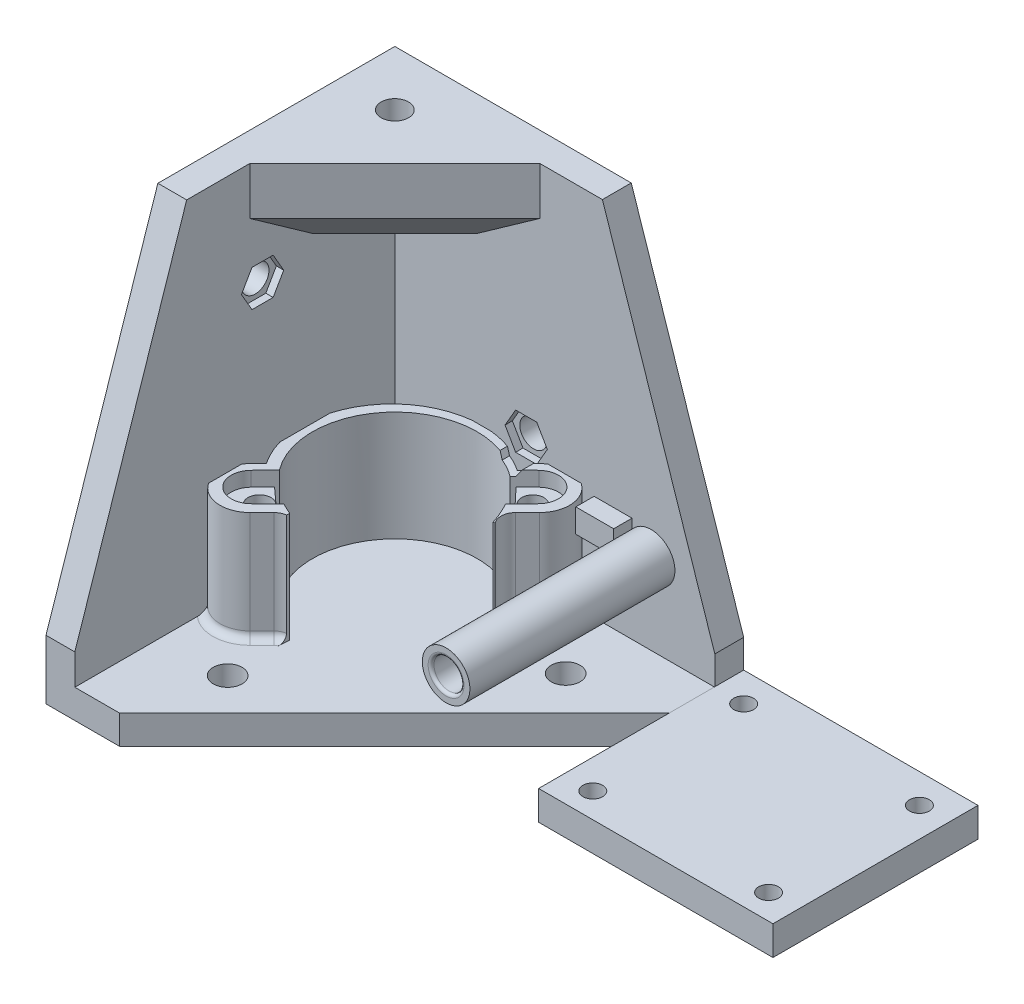
SolidWorks part; units mm, degrees
ref_plane "Front" through (0, 0, 0) normal (0, 0, 1) x (1, 0, 0)
ref_plane "Top" through (0, 0, 0) normal (0, 1, 0) x (1, 0, 0)
ref_plane "Right" through (0, 0, 0) normal (1, 0, 0) x (0, 0, -1)
sketch "Sketch1" plane through (0, 0, 0) normal (0, 1, 0) x (1, 0, 0)
  line L0 (0, 0) -> (0, 60.5)
  line L1 (0, -55) -> (0, 55) construction
  line L2 (0, 60.5) -> (60.5, 60.5)
  line L3 (60.5, 60.5) -> (60.5, 47.75)
  line L4 (60.5, 47.75) -> (12.75, 0)
  line L5 (-55, 0) -> (55, 0) construction
  line L6 (12.75, 0) -> (0, 0)
  dimension "D1" = 60.5
  dimension "D2" = 12.75
extrude "Boss-Extrude1" add sketch "Sketch1" along normal blind 5
sketch "Sketch4" plane through (0, 0, 0) normal (-1, 0, 0) x (0, 0, 1)
  line L0 (-60.5, 5) -> (-60.5, 68.5)
  line L1 (-60.5, 68.5) -> (-19.4, 68.5)
  line L2 (-19.4, 68.5) -> (0, 10.3086)
  line L3 (0, 10.3086) -> (0, 5)
  line L4 (0, -2.75) -> (0, 2.75) construction
  line L5 (-60.5, 5) -> (0, 5) construction
  line L6 (-60.5, 5) -> (0, 5)
  dimension "D1" = 63.5
  dimension "D2" = 41.1
  dimension "D3" = 61.34
extrude "Boss-Extrude2" add sketch "Sketch4" against normal blind 5
sketch "Sketch5" plane through (0, 0, -60.5) normal (0, 0, -1) x (-1, 0, 0)
  line L0 (0, 68.5) -> (-41, 68.5)
  line L1 (-41, 68.5) -> (-60.5, 10.0047)
  line L2 (-60.5, 10.0047) -> (-60.5, 5)
  line L6 (-60.5, 0) -> (0, 0)
  line L7 (0, 0) -> (0, 68.5)
  line L8 (0, 68.5) -> (-5, 68.5)
  line L9 (-5, 68.5) -> (-5, 5)
  line L10 (-5, 5) -> (-60.5, 5)
  line L11 (-60.5, 5) -> (-60.5, 0)
  line L12 (-60.5, 0) -> (0, 0)
  line L13 (0, 0) -> (0, 68.5)
  line L14 (0, 68.5) -> (-5, 68.5)
  line L15 (-5, 68.5) -> (-5, 5)
  line L16 (-5, 5) -> (-60.5, 5)
  line L17 (-60.5, 5) -> (-60.5, 0)
  line M13 (-5, 68.5) -> (-5, 5)
  line M14 (-5, 5) -> (-60.5, 5)
  dimension "D2" = 41
  dimension "D3" = 61.66
  dimension "D1" = 0
extrude "Boss-Extrude3" add sketch "Sketch5" against normal blind 5 contours L1 L2 L0 M14 M13
sketch "Sketch6" plane through (0, 5, 0) normal (0, 1, 0) x (1, 0, 0)
  line L0 (60.5, 60.5) -> (0, 60.5) construction
  line L4 (0, 19.4) -> (0, 0)
  line L5 (60.5, 55.5) -> (5, 55.5)
  line L6 (5, 55.5) -> (5, 0)
  line L7 (5, 0) -> (12.75, 0)
  line L8 (12.75, 0) -> (60.5, 47.75)
  line L9 (60.5, 47.75) -> (60.5, 55.5)
  line L10 (60.5, 55.5) -> (5, 55.5)
  line L11 (5, 55.5) -> (5, 0)
  line L12 (5, 0) -> (12.75, 0)
  line L13 (12.75, 0) -> (60.5, 47.75)
  line L14 (60.5, 47.75) -> (60.5, 55.5)
  line L15 (0, 0) -> (5, 0)
  line L16 (5, 0) -> (5, 19.4)
  line L17 (5, 19.4) -> (0, 19.4)
  line L18 (0, 19.4) -> (0, 0)
  line L19 (0, 0) -> (5, 0)
  line L20 (5, 0) -> (5, 19.4)
  line L21 (5, 19.4) -> (0, 19.4)
  line L24 (0, 60.5) -> (0, 19.4)
  line L25 (0, 19.4) -> (5, 19.4)
  line L26 (5, 19.4) -> (5, 55.5)
  line L27 (5, 55.5) -> (41, 55.5)
  line L28 (41, 55.5) -> (41, 60.5)
  line L29 (41, 60.5) -> (0, 60.5)
  line L30 (0, 60.5) -> (0, 19.4)
  line L31 (0, 19.4) -> (5, 19.4)
  line L32 (5, 19.4) -> (5, 55.5)
  line L33 (5, 55.5) -> (41, 55.5)
  line L34 (41, 55.5) -> (41, 60.5)
  line L35 (41, 60.5) -> (0, 60.5)
  circle A0 centre (16.5, 15) radius 2.5
  circle A1 centre (45.5, 44.625) radius 2.5
  dimension "D1" = 5
  dimension "D2" = 5
  dimension "D3" = 0
  dimension "D4" = 15
  dimension "D6" = 16.5
  dimension "D7" = 15
  dimension "D9" = 15.875
  dimension "D5" = 0
  dimension "D8" = 0
extrude "Cut-Extrude1" cut sketch "Sketch6" against normal through all contours A0 | A1
sketch "Sketch9" plane through (0, 0, -55.5) normal (0, 0, 1) x (1, 0, 0)
  line L1 (5, 68.5) -> (5, 5) construction
  line L5 (0, 0) -> (60.5, 0)
  line L6 (0, 68.5) -> (0, 0)
  line L7 (41, 68.5) -> (0, 68.5)
  line L8 (60.5, 10.0047) -> (41, 68.5)
  line L9 (60.5, 0) -> (60.5, 10.0047)
  line L10 (0, 0) -> (60.5, 0)
  line L11 (0, 68.5) -> (0, 0)
  line L12 (41, 68.5) -> (0, 68.5)
  line L13 (60.5, 10.0047) -> (41, 68.5)
  line L14 (60.5, 0) -> (60.5, 10.0047)
  line L15 (49.45, 19.0462) -> (49.45, 11.3161) construction
  circle A0 centre (49.45, 19.0462) radius 4.1275
  circle A1 centre (49.45, 19.0462) radius 2.6035
  dimension "D2" = 5.207
  dimension "D3" = 1.524
  dimension "D4" = 49.4538
  dimension "D5" = 44.45
  dimension "D1" = 0
extrude "Boss-Extrude5" add sketch "Sketch9" along normal blind 35.56
fillet "Fillet1" radius 0.508 1 edges at (52.0535, 19.0462, -19.94)
sketch "Sketch14" plane through (0, 5, 0) normal (0, 1, 0) x (1, 0, 0)
  line L0 (13.4627, 27.5396) -> (14.7681, 26.7924)
  line L1 (12.75, 0) -> (60.5, 47.75) construction
  line L2 (36.625, 23.875) -> (5, 55.5) construction
  line L3 (5, 55.5) -> (60.5, 55.5) construction
  line L4 (32.9604, 47.0373) -> (33.7076, 45.7319)
  line L5 (14.8281, 26.8523) -> (11.8274, 23.8516)
  line L6 (6.723, 28.8027) -> (9.1327, 31.3641)
  line L7 (33.6477, 45.6719) -> (36.6484, 48.6726)
  line L8 (31.6973, 53.777) -> (29.1359, 51.3673)
  line L9 (15.0744, 24.4582) -> (13.006, 22.3898)
  line L10 (5.6561, 29.7396) -> (7.0609, 31.1444)
  line L11 (36.0418, 45.4256) -> (38.1102, 47.494)
  line L12 (30.7604, 54.8439) -> (28.83, 52.9135)
  line L13 (18.1324, 24.8665) -> (30.5234, 17.7734)
  line L14 (35.6335, 42.3676) -> (42.7266, 29.9766)
  line L15 (31.7409, 18.9909) -> (18.852, 25.7543)
  line L16 (41.5091, 28.7591) -> (34.7457, 41.648)
  line L17 (16.5689, 25.6946) -> (16.5343, 25.1798)
  line L18 (34.7457, 41.648) -> (35.7996, 42.0774)
  circle A0 centre (20.5607, 39.9393) radius 14.2875
  arc A1 (11.8274, 23.8516) -> (6.723, 28.8027) centre (9.3129, 26.3661) cw
  arc A2 (36.6484, 48.6726) -> (31.6973, 53.777) centre (34.1339, 51.1871) ccw
  arc A3 (13.006, 22.3898) -> (5.6561, 29.7396) centre (9.3311, 26.0647) cw
  arc A4 (38.1102, 47.494) -> (30.7604, 54.8439) centre (34.4353, 51.1689) ccw
  arc A5 (7.0609, 31.1444) -> (28.83, 52.9135) centre (20.0709, 39.9035) cw
  arc A6 (36.0418, 45.4256) -> (35.6335, 42.3676) centre (37.8378, 43.6295) ccw
  arc A7 (15.0744, 24.4582) -> (18.1324, 24.8665) centre (16.8705, 22.6622) cw
  arc A9 (33.8602, 45.8844) -> (36.3595, 38.5726) centre (13.6025, 34.877) cw
  arc A10 (14.6156, 26.6398) -> (21.9274, 24.1405) centre (25.623, 46.8975) ccw
  point P40 (34.6689, 44.0527)
  point P43 (16.4473, 25.8311)
  line M13 (60.5, 55.5) -> (5, 55.5)
  line M14 (5, 55.5) -> (5, 0)
  line M16 (12.75, 0) -> (60.5, 47.75)
  dimension "D1" = 28.575
  dimension "D2" = 3.556
  dimension "D3" = 2.54
extrude "Boss-Extrude6" add sketch "Sketch14" along normal blind 19.05 contours L2 A0 L5 A1 L6 A5 L10 A3 L9 A7 L13 M16 M14 | L2 L14 A6 L11 A4 L12 A5 A0 L8 A2 L7 M16 M13
sketch "Sketch15" plane through (0, 68.5, 0) normal (0, 1, 0) x (1, 0, 0)
  line L0 (5, 30.3375) -> (30.1625, 55.5)
  line L1 (0, -33.275) -> (0, 33.275) construction
  line L2 (41, 60.5) -> (0, 60.5) construction
  line L6 (0, 60.5) -> (0, 19.4)
  line L7 (0, 19.4) -> (5, 19.4)
  line L8 (5, 19.4) -> (5, 55.5)
  line L9 (5, 55.5) -> (41, 55.5)
  line L10 (41, 55.5) -> (41, 60.5)
  line L11 (41, 60.5) -> (0, 60.5)
  line L13 (0, 19.4) -> (5, 19.4)
  line L14 (5, 30.3375) -> (5, 55.5)
  line L15 (5, 55.5) -> (30.1625, 55.5)
  line L16 (41, 55.5) -> (41, 60.5)
  circle A0 centre (9.525, 50.975) radius 2.3812
  line M11 (5, 19.4) -> (5, 55.5)
  line M12 (5, 55.5) -> (41, 55.5)
  dimension "D3" = 4.7625
  dimension "D4" = 9.525
  dimension "D5" = 9.525
  dimension "D2" = 45
  dimension "D1" = 0
extrude "Boss-Extrude7" add sketch "Sketch15" against normal blind 15.875 contours L0 A0 M11 M12
chamfer "Chamfer2" distance 7.62 angle 45 1 edges at (17.5813, 52.625, -42.9187)
fillet "Fillet2" radius 1.27 7 edges at (39.6065, 5, -51.6871) (37.076, 5, -46.4598) (35.3202, 5, -43.9657) (8.8129, 5, -20.8935) (14.0402, 5, -23.424) (15.745, 5, -24.9392) (35.7165, 5, -42.2225)
sketch "Sketch16" plane through (0, 0, -55.5) normal (0, 0, 1) x (1, 0, 0)
  line L1 (46.1305, 23.2107) -> (38.2864, 23.2107)
  line L2 (46.1305, 23.2107) -> (46.1305, 19.0978)
  line L3 (46.1305, 19.0978) -> (38.2864, 19.0978)
  line L4 (38.2864, 23.2107) -> (38.2864, 19.0978)
extrude "Boss-Extrude8" add sketch "Sketch16" along normal blind 3.175
chamfer "Chamfer3" distance 1.27 angle 45 1 edges at (38.2864, 23.2107, -55.0794)
sketch "Sketch17" plane through (0, 5, 0) normal (0, 1, 0) x (1, 0, 0)
  line L0 (8.716, 30.9212) -> (14.047, 26.0712)
  line L1 (36.625, 23.875) -> (5, 55.5) construction
  line L2 (12.75, 0) -> (60.5, 47.75) construction
  line L3 (5, 55.5) -> (18.418, 55.5) construction
  line L4 (5, 55.5) -> (5, 44.2452) construction
  line L5 (29.6632, 51.8634) -> (34.5959, 46.6202)
  line L22 (37.3079, 55.5) -> (31.5627, 55.5)
  line L23 (30.7604, 54.8439) -> (28.83, 52.9135)
  line L24 (21.7238, 55.5) -> (18.418, 55.5)
  line L25 (5, 44.2452) -> (5, 35.5618)
  line L26 (7.0609, 31.1444) -> (5.6561, 29.7396)
  line L27 (5, 28.9373) -> (5, 23.1921)
  line L28 (13.006, 22.3898) -> (15.0744, 24.4582)
  line L29 (16.5343, 25.1798) -> (16.5689, 25.6946)
  line L30 (16.5343, 25.1798) -> (16.5689, 25.6946)
  line L31 (35.539, 41.9712) -> (35.7996, 42.0774)
  line L32 (35.539, 41.9712) -> (35.7996, 42.0774)
  line L33 (14.6156, 26.6398) -> (11.8274, 23.8516)
  line L34 (6.723, 28.8027) -> (9.1327, 31.3641)
  line L35 (29.1359, 51.3673) -> (31.6973, 53.777)
  line L36 (36.6484, 48.6726) -> (33.8602, 45.8844)
  line L40 (35.7996, 42.0774) -> (35.6335, 42.3676)
  line L41 (36.0418, 45.4256) -> (38.1102, 47.494)
  line L43 (37.3079, 55.5) -> (31.5627, 55.5)
  line L44 (30.7604, 54.8439) -> (28.83, 52.9135)
  line L45 (21.7238, 55.5) -> (18.418, 55.5)
  line L46 (5, 44.2452) -> (5, 35.5618)
  line L47 (7.0609, 31.1444) -> (5.6561, 29.7396)
  line L48 (5, 28.9373) -> (5, 23.1921)
  line L49 (13.006, 22.3898) -> (15.0744, 24.4582)
  line L54 (14.6156, 26.6398) -> (11.8274, 23.8516)
  line L55 (6.723, 28.8027) -> (9.1327, 31.3641)
  line L56 (29.1359, 51.3673) -> (31.6973, 53.777)
  line L57 (36.6484, 48.6726) -> (33.8602, 45.8844)
  line L61 (35.7996, 42.0774) -> (35.6335, 42.3676)
  line L62 (36.0418, 45.4256) -> (38.1102, 47.494)
  circle A1 centre (33.6908, 50.7324) radius 2.1828
  circle A2 centre (10.0204, 27.0078) radius 1.9844
  circle A3 centre (33.6908, 50.7324) radius 1.9288
  arc A15 (38.1102, 47.494) -> (37.3079, 55.5) centre (34.4353, 51.1689) ccw
  arc A17 (31.5627, 55.5) -> (30.7604, 54.8439) centre (34.4353, 51.1689) ccw
  arc A18 (28.83, 52.9135) -> (21.7238, 55.5) centre (20.0709, 39.9035) ccw
  arc A19 (18.418, 55.5) -> (5, 44.2452) centre (20.0709, 39.9035) ccw
  arc A20 (5, 35.5618) -> (7.0609, 31.1444) centre (20.0709, 39.9035) ccw
  arc A21 (5.6561, 29.7396) -> (5, 28.9373) centre (9.3311, 26.0647) ccw
  arc A22 (5, 23.1921) -> (13.006, 22.3898) centre (9.3311, 26.0647) ccw
  arc A23 (16.5343, 25.1798) -> (15.0744, 24.4582) centre (16.8705, 22.6622) ccw
  arc A24 (14.6156, 26.6398) -> (16.5689, 25.6946) centre (25.623, 46.8975) ccw
  arc A25 (6.723, 28.8027) -> (11.8274, 23.8516) centre (9.3129, 26.3661) ccw
  arc A26 (29.1359, 51.3673) -> (9.1327, 31.3641) centre (20.5607, 39.9393) ccw
  arc A27 (36.6484, 48.6726) -> (31.6973, 53.777) centre (34.1339, 51.1871) ccw
  arc A28 (35.539, 41.9712) -> (33.8602, 45.8844) centre (13.6025, 34.877) ccw
  arc A29 (36.0418, 45.4256) -> (35.6335, 42.3676) centre (37.8378, 43.6295) ccw
  arc A30 (38.1102, 47.494) -> (37.3079, 55.5) centre (34.4353, 51.1689) ccw
  arc A32 (31.5627, 55.5) -> (30.7604, 54.8439) centre (34.4353, 51.1689) ccw
  arc A33 (28.83, 52.9135) -> (21.7238, 55.5) centre (20.0709, 39.9035) ccw
  arc A34 (18.418, 55.5) -> (5, 44.2452) centre (20.0709, 39.9035) ccw
  arc A35 (5, 35.5618) -> (7.0609, 31.1444) centre (20.0709, 39.9035) ccw
  arc A36 (5.6561, 29.7396) -> (5, 28.9373) centre (9.3311, 26.0647) ccw
  arc A37 (5, 23.1921) -> (13.006, 22.3898) centre (9.3311, 26.0647) ccw
  arc A38 (16.5343, 25.1798) -> (15.0744, 24.4582) centre (16.8705, 22.6622) ccw
  arc A39 (14.6156, 26.6398) -> (16.5689, 25.6946) centre (25.623, 46.8975) ccw
  arc A40 (6.723, 28.8027) -> (11.8274, 23.8516) centre (9.3129, 26.3661) ccw
  arc A41 (29.1359, 51.3673) -> (9.1327, 31.3641) centre (20.5607, 39.9393) ccw
  arc A42 (36.6484, 48.6726) -> (31.6973, 53.777) centre (34.1339, 51.1871) ccw
  arc A43 (35.539, 41.9712) -> (33.8602, 45.8844) centre (13.6025, 34.877) ccw
  arc A44 (36.0418, 45.4256) -> (35.6335, 42.3676) centre (37.8378, 43.6295) ccw
  dimension "D2" = 3.9688
  dimension "D3" = 0.254
  dimension "D1" = 0
extrude "Boss-Extrude9" add sketch "Sketch17" along normal offset from surface (16.51 mm away) 2.54
sketch "Sketch18" plane through (0, 0, 0) normal (-1, 0, 0) x (0, 0, 1)
  line L0 (-60.5, 68.5) -> (-60.5, 0) construction
  line L1 (33.275, 0) -> (-33.275, 0) construction
  circle A0 centre (-32.56, 49.53) radius 2.3813
  dimension "D1" = 27.94
  dimension "D2" = 49.53
  dimension "D3" = 4.7625
extrude "Cut-Extrude2" cut sketch "Sketch18" against normal up to next
sketch "Sketch19" plane through (0, 0, -60.5) normal (0, 0, -1) x (-1, 0, 0)
  line L0 (0, 33.275) -> (0, -33.275) construction
  line L1 (33.275, 0) -> (-33.275, 0) construction
  circle A0 centre (-27.7812, 26.1937) radius 2.3813
  dimension "D1" = 27.7812
  dimension "D2" = 26.1937
  dimension "D3" = 4.7625
extrude "Cut-Extrude3" cut sketch "Sketch19" against normal up to next
sketch "Sketch20" plane through (0, 0, -55.5) normal (0, 0, 1) x (1, 0, 0)
  line L1 (31.4474, 26.1937) -> (29.6143, 29.3687)
  line L2 (29.6143, 29.3687) -> (25.9482, 29.3687)
  line L3 (25.9482, 29.3687) -> (24.1151, 26.1937)
  line L4 (24.1151, 26.1937) -> (25.9482, 23.0187)
  line L5 (25.9482, 23.0187) -> (29.6143, 23.0187)
  line L6 (29.6143, 23.0187) -> (31.4474, 26.1937)
  circle A0 centre (27.7812, 26.1937) radius 2.3813 construction
  circle A1 centre (27.7812, 26.1937) radius 2.3813
  circle A2 centre (27.7812, 26.1937) radius 3.175 construction
  dimension "D1" = 6.35
extrude "Cut-Extrude4" cut sketch "Sketch20" against normal blind 1.27 and the other way up to vertex (4.1327 mm away) contours L1 L2 L3 L4 L5 L6 other way up to point (29.1359, 5, -51.3673)
sketch "Sketch21" plane through (5, 0, 0) normal (1, 0, 0) x (0, 0, -1)
  line L1 (34.3931, 52.705) -> (30.7269, 52.705)
  line L2 (30.7269, 52.705) -> (28.8938, 49.53)
  line L3 (28.8938, 49.53) -> (30.7269, 46.355)
  line L4 (30.7269, 46.355) -> (34.3931, 46.355)
  line L5 (34.3931, 46.355) -> (36.2262, 49.53)
  line L6 (36.2262, 49.53) -> (34.3931, 52.705)
  circle A0 centre (32.56, 49.53) radius 2.3813 construction
  circle A1 centre (32.56, 49.53) radius 2.3812
  circle A2 centre (32.56, 49.53) radius 3.175 construction
  dimension "D1" = 6.35
extrude "Cut-Extrude5" cut sketch "Sketch21" against normal blind 1.27 contours L1 L2 L3 L4 L5 L6
sketch "Sketch23" plane through (0, 0, 0) normal (0, 1, 0) x (1, 0, 0)
  line L1 (60.5, 60.5) -> (101.14, 60.5)
  line L2 (60.5, 60.5) -> (60.5, 24.94)
  line L3 (60.5, 24.94) -> (101.14, 24.94)
  line L4 (101.14, 60.5) -> (101.14, 24.94)
  dimension "D1" = 40.64
  dimension "D2" = 35.56
extrude "Boss-Extrude12" add sketch "Sketch23" along normal blind 5.08
sketch "Sketch24" plane through (0, 5.08, 0) normal (0, 1, 0) x (1, 0, 0)
  line L0 (101.14, 60.5) -> (60.5, 60.5) construction
  line L1 (60.5, 47.75) -> (60.5, 55.5) construction
  circle A0 centre (65.58, 55.42) radius 1.7145
  circle A1 centre (96.06, 55.42) radius 1.7145
  circle A2 centre (96.06, 29.258) radius 1.7145
  circle A3 centre (65.58, 29.258) radius 1.7145
  dimension "D1" = 3.429
  dimension "D2" = 26.162
  dimension "D3" = 30.48
  dimension "D4" = 5.08
  dimension "D5" = 5.08
extrude "Cut-Extrude6" cut sketch "Sketch24" against normal up to next
